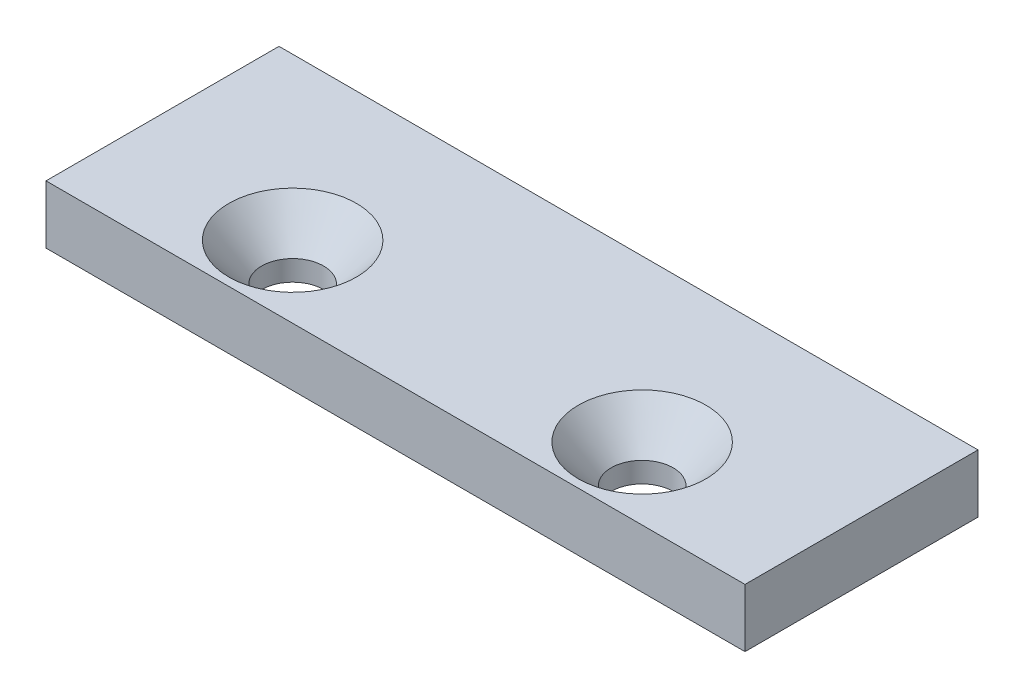
SolidWorks part; units mm, degrees
material "6061 Alloy"
ref_plane "Front Plane" through (0, 0, 0) normal (0, 0, 1) x (1, 0, 0)
ref_plane "Top Plane" through (0, 0, 0) normal (0, 1, 0) x (1, 0, 0)
ref_plane "Right Plane" through (0, 0, 0) normal (1, 0, 0) x (0, 0, -1)
sketch "Sketch1" plane through (0, 0, 0) normal (0, 1, 0) x (1, 0, 0)
  line L1 (0, 0) -> (76.2, 0)
  line L2 (0, 0) -> (0, 25.4)
  line L3 (0, 25.4) -> (76.2, 25.4)
  line L4 (76.2, 0) -> (76.2, 25.4)
  point P5 (57.15, 9.525)
  point P8 (19.05, 9.525)
  dimension "D1" = 25.4
  dimension "D2" = 76.2
  dimension "D3" = 19.05
  dimension "D4" = 9.525
  dimension "D5" = 19.05
  dimension "D6" = 9.525
extrude "Boss-Extrude1" add sketch "Sketch1" against normal blind 6.35
hole_wizard "CSK for 1/4 Flat Head Machine Screw1" positions "Sketch2" profile "Sketch3" countersink size "1/4" standard "ANSI Inch" end condition through all
sketch "Sketch2" plane through (0, 0, 0) normal (0, 1, 0) x (1, 0, 0)
  line L1 (0, 25.4) -> (0, 0) construction
  line L2 (76.2, 0) -> (76.2, 25.4) construction
  point P0 (19.05, 7.8393)
  point P2 (57.15, 7.8393)
  dimension "D3" = 19.05
  dimension "D4" = 19.05
sketch "Sketch3" plane through (19.05, 0, -7.8393) normal (1, 0, 0) x (0, 0, 1)
  line L0 (0, 0) -> (0, 6.35)
  line L1 (0, 6.35) -> (3.3782, 6.35)
  line L2 (3.3782, 6.35) -> (3.3782, 4.1199)
  line L3 (3.3782, 4.1199) -> (6.9596, 0)
  line L5 (6.9596, 0) -> (0, 0)
  line L6 (-3.3782, 4.1199) -> (-6.9596, 0) construction
  line L11 (0, -6.35) -> (0, 107.95) construction
  dimension "Thru Hole Dia." = 6.7564
  dimension "Thru Hole Depth" = 6.35
  dimension "Near C'Sink Dia." = 13.9192
  dimension "Near C'Sink Angle" = 82
